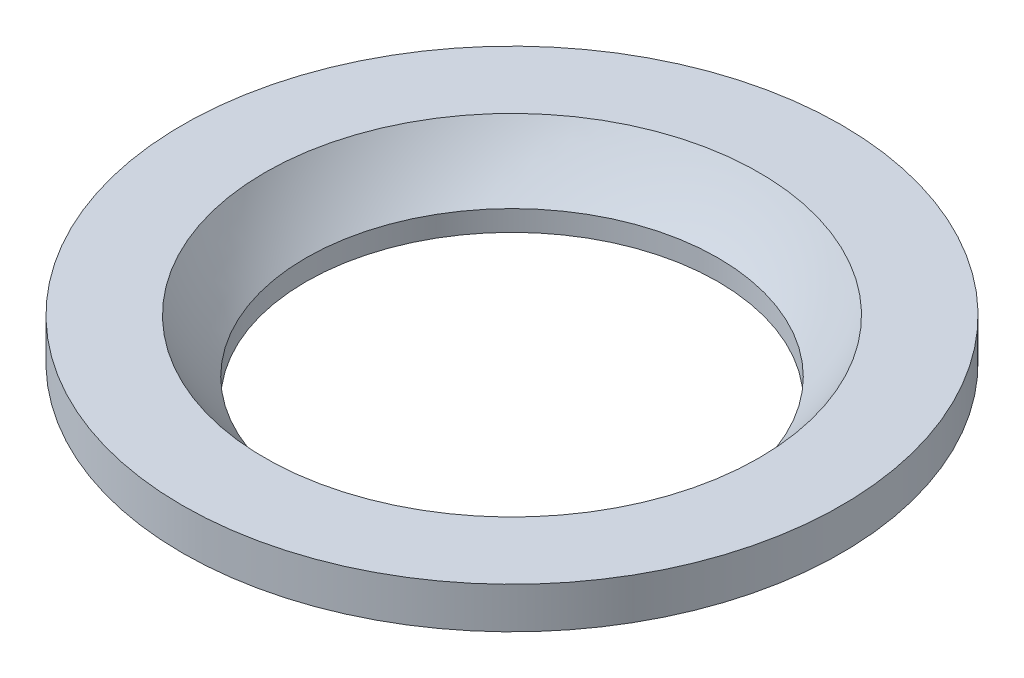
SolidWorks part; units mm, degrees
ref_plane "Plan de face" through (0, 0, 0) normal (0, 0, 1) x (1, 0, 0)
ref_plane "Plan de dessus" through (0, 0, 0) normal (0, 1, 0) x (1, 0, 0)
ref_plane "Plan de droite" through (0, 0, 0) normal (1, 0, 0) x (0, 0, -1)
sketch "Esquisse1" plane through (0, 0, 0) normal (0, 0, 1) x (1, 0, 0)
  line L0 (6, -3.6056) -> (8, -3.6056)
  line L1 (8, -3.6056) -> (8, -4.6056)
  line L2 (8, -4.6056) -> (7.5, -4.6056)
  line L3 (5, -4.899) -> (5, -5.399)
  line L4 (0, 0) -> (0, -2.5704) construction
  arc A0 (5, -4.899) -> (6, -3.6056) centre (0, 0) ccw
  arc A1 (7.5, -4.6056) -> (5, -5.399) centre (5.1069, -1.4004) cw
  dimension "D6" = 0.5
  dimension "D1" = 7
  dimension "D8" = 4
  dimension "D2" = 5
  dimension "D3" = 6
  dimension "D4" = 8
  dimension "D5" = 1
  dimension "D7" = 0.5
revolve "Révolution1" add sketch "Esquisse1" angle 360 about L4
